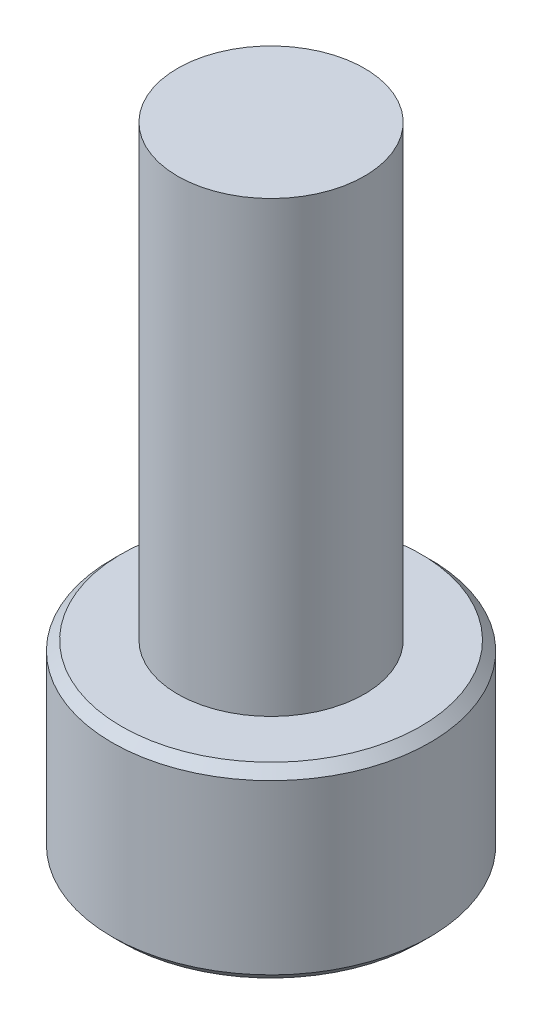
SolidWorks part; units mm, degrees
ref_plane "前视基准面" through (0, 0, 0) normal (0, 0, 1) x (1, 0, 0)
ref_plane "上视基准面" through (0, 0, 0) normal (0, 1, 0) x (1, 0, 0)
ref_plane "右视基准面" through (0, 0, 0) normal (1, 0, 0) x (0, 0, -1)
other "Configuration Table"
sketch "草图1" plane through (0, 0, 0) normal (0, 1, 0) x (1, 0, 0)
  circle A0 centre (0, 0) radius 4.25
  dimension "D1" = 8.5
extrude "凸台-拉伸1" add sketch "草图1" against normal blind 5
sketch "草图2" plane through (0, 0, 0) normal (0, 1, 0) x (1, 0, 0)
  circle A0 centre (0, 0) radius 2.5
  dimension "D1" = 5
extrude "凸台-拉伸2" add sketch "草图2" along normal blind 12
sketch "草图3" plane through (0, 0, 0) normal (0, 1, 0) x (1, 0, 0)
  line L1 (2, -1.1547) -> (2, 1.1547)
  line L2 (2, 1.1547) -> (0, 2.3094)
  line L3 (0, 2.3094) -> (-2, 1.1547)
  line L4 (-2, 1.1547) -> (-2, -1.1547)
  line L5 (-2, -1.1547) -> (0, -2.3094)
  line L6 (0, -2.3094) -> (2, -1.1547)
  circle A0 centre (0, 0) radius 2 construction
  dimension "D1" = 4
extrude "切除-拉伸1" cut sketch "草图3" along normal blind 2.5 from surface at -5 starting at face at (0, -5, 4.25)
chamfer "倒角1" distance 0.25 angle 45 2 edges at (0, 0, 4.25) (0, -5, 4.25)
